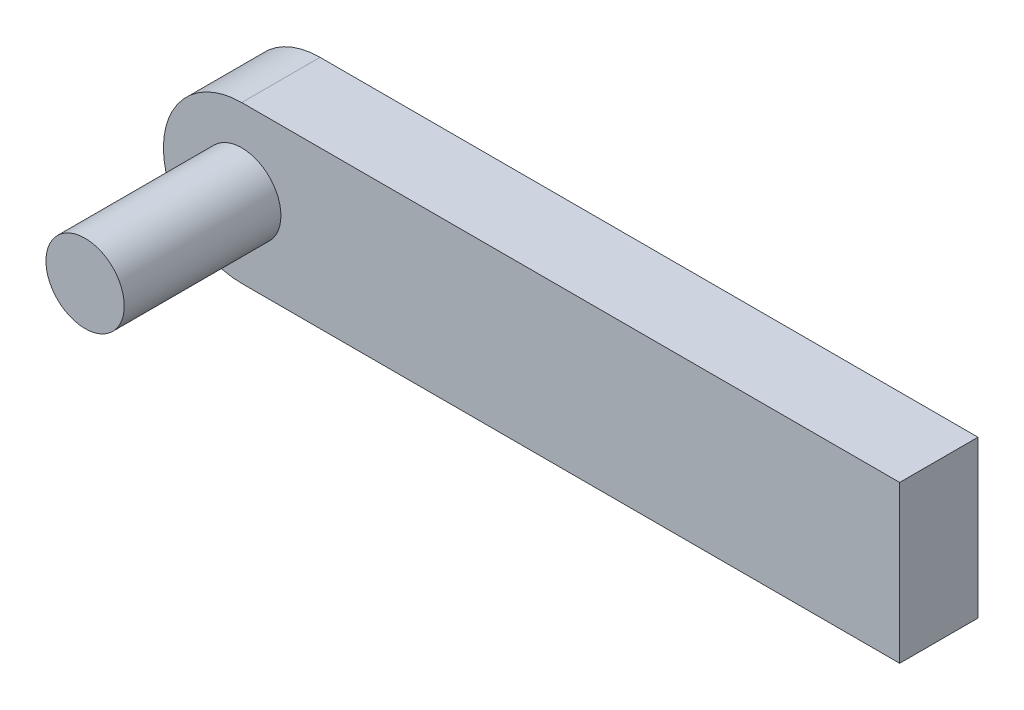
SolidWorks part; units mm, degrees
ref_plane "Front Plane" through (0, 0, 0) normal (0, 0, 1) x (1, 0, 0)
ref_plane "Top Plane" through (0, 0, 0) normal (0, 1, 0) x (1, 0, 0)
ref_plane "Right Plane" through (0, 0, 0) normal (1, 0, 0) x (0, 0, -1)
sketch "Sketch1" plane through (0, 0, 0) normal (0, 0, 1) x (1, 0, 0)
  circle A0 centre (0, 0) radius 2.5
  dimension "D1" = 5
extrude "Boss-Extrude1" add sketch "Sketch1" along normal blind 10
sketch "Sketch2" plane through (0, 0, 0) normal (0, 0, -1) x (-1, 0, 0)
  circle A0 centre (0, 0) radius 5
  dimension "D1" = 10
extrude "Boss-Extrude2" add sketch "Sketch2" along normal blind 5
ref_plane "Plane1" through (10, 0, 0) normal (1, 0, 0) x (0, 0, -1)
sketch "Sketch4" plane through (10, 0, 0) normal (1, 0, 0) x (0, 0, -1)
  line L1 (0, 5) -> (5, 5)
  line L2 (0, 5) -> (0, -5)
  line L3 (0, -5) -> (5, -5)
  line L4 (5, 5) -> (5, -5)
  dimension "D1" = 10
extrude "Boss-Extrude3" add sketch "Sketch4" against normal up to surface (10 mm away)
sketch "Sketch5" plane through (10, 0, 0) normal (1, 0, 0) x (0, 0, -1)
  line L1 (0, 5) -> (5, 5)
  line L2 (0, 5) -> (0, -5)
  line L3 (0, -5) -> (5, -5)
  line L4 (5, 5) -> (5, -5)
extrude "Boss-Extrude4" add sketch "Sketch5" along normal blind 32
